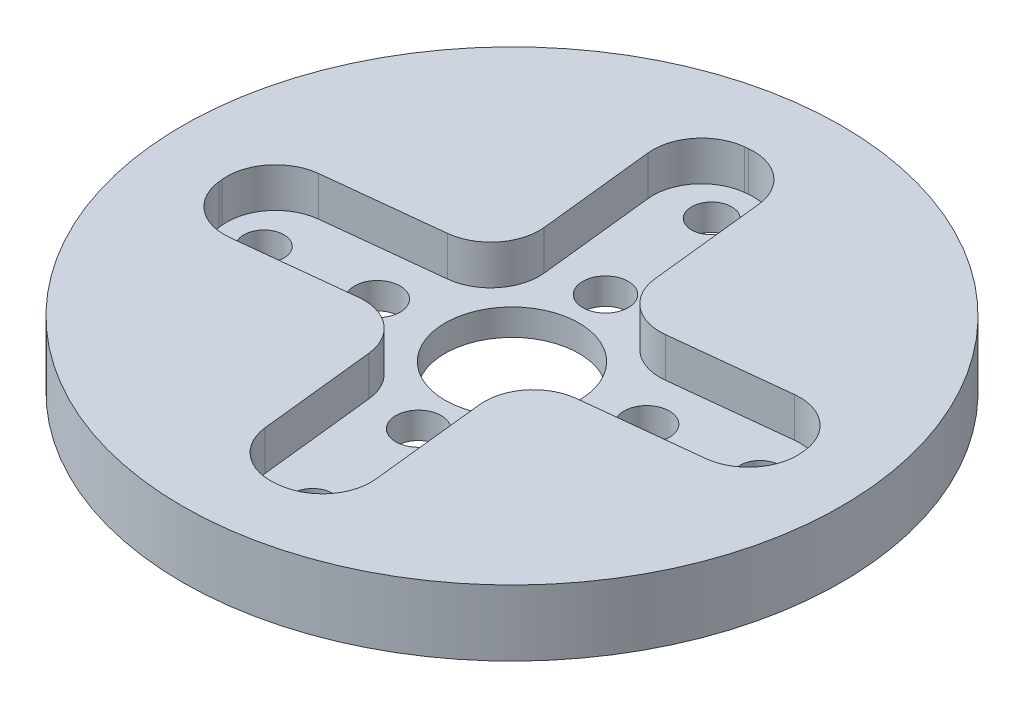
SolidWorks part; units mm, degrees
ref_plane "前基準面" through (0, 0, 0) normal (0, 0, 1) x (1, 0, 0)
ref_plane "上基準面" through (0, 0, 0) normal (0, 1, 0) x (1, 0, 0)
ref_plane "右基準面" through (0, 0, 0) normal (1, 0, 0) x (0, 0, -1)
sketch "草圖1" plane through (0, 0, 0) normal (0, 1, 0) x (1, 0, 0)
  line L38 (-19.9629, -2.0351) -> (-19.9356, -2.2876)
  line L39 (-15.8773, -5.5525) -> (-7.039, -4.5949)
  line L40 (-2.9807, -7.8598) -> (-2.0232, -16.6981)
  line L41 (2.0351, -19.9629) -> (2.2876, -19.9356)
  line L42 (5.5525, -15.8773) -> (4.5949, -7.039)
  line L43 (7.8598, -2.9807) -> (16.6981, -2.0232)
  line L44 (19.9629, 2.0351) -> (19.9356, 2.2876)
  line L45 (15.8773, 5.5525) -> (7.039, 4.5949)
  line L46 (2.9807, 7.8598) -> (2.0232, 16.6981)
  line L47 (-2.0351, 19.9629) -> (-2.2876, 19.9356)
  line L48 (-5.5525, 15.8773) -> (-4.5949, 7.039)
  line L49 (-7.8598, 2.9807) -> (-16.6981, 2.0232)
  circle A0 centre (0, 0) radius 25
  arc A25 (-16.6981, 2.0232) -> (-19.9629, -2.0351) centre (-16.3014, -1.6384) ccw
  arc A26 (-19.9356, -2.2876) -> (-15.8773, -5.5525) centre (-16.274, -1.8909) ccw
  arc A27 (-2.9807, -7.8598) -> (-7.039, -4.5949) centre (-6.6423, -8.2565) ccw
  arc A28 (-2.0232, -16.6981) -> (2.0351, -19.9629) centre (1.6384, -16.3014) ccw
  arc A29 (2.2876, -19.9356) -> (5.5525, -15.8773) centre (1.8909, -16.274) ccw
  arc A30 (7.8598, -2.9807) -> (4.5949, -7.039) centre (8.2565, -6.6423) ccw
  arc A31 (16.6981, -2.0232) -> (19.9629, 2.0351) centre (16.3014, 1.6384) ccw
  arc A32 (19.9356, 2.2876) -> (15.8773, 5.5525) centre (16.274, 1.8909) ccw
  arc A33 (2.9807, 7.8598) -> (7.039, 4.5949) centre (6.6423, 8.2565) ccw
  arc A34 (2.0232, 16.6981) -> (-2.0351, 19.9629) centre (-1.6384, 16.3014) ccw
  arc A35 (-2.2876, 19.9356) -> (-5.5525, 15.8773) centre (-1.8909, 16.274) ccw
  arc A36 (-7.8598, 2.9807) -> (-4.5949, 7.039) centre (-8.2565, 6.6423) ccw
  point P3 (0, 0)
  dimension "D1" = 50
extrude "填料-伸長1" add sketch "草圖1" along normal blind 5
sketch "草圖3" plane through (0, 0, 0) normal (0, 1, 0) x (1, 0, 0)
  circle A0 centre (0, 0) radius 22.5
  circle A1 centre (16.9821, 1.8399) radius 1.524 construction
  circle A2 centre (9.2171, 0.9986) radius 1.7272 construction
  circle A3 centre (1.8399, -16.9821) radius 1.524 construction
  circle A4 centre (0.8618, -7.9545) radius 1.7272 construction
  circle A5 centre (0, 0) radius 5.08 construction
  circle A6 centre (-16.9821, -1.8399) radius 1.524 construction
  circle A7 centre (-9.2171, -0.9986) radius 1.7272 construction
  circle A8 centre (-1.8399, 16.9821) radius 1.524 construction
  circle A9 centre (-0.8618, 7.9545) radius 1.7272 construction
  circle A10 centre (16.9821, 1.8399) radius 1.524
  circle A11 centre (9.2171, 0.9986) radius 1.7272
  circle A12 centre (1.8399, -16.9821) radius 1.524
  circle A13 centre (0.8618, -7.9545) radius 1.7272
  circle A14 centre (0, 0) radius 5.08
  circle A15 centre (-16.9821, -1.8399) radius 1.524
  circle A16 centre (-9.2171, -0.9986) radius 1.7272
  circle A17 centre (-1.8399, 16.9821) radius 1.524
  circle A18 centre (-0.8618, 7.9545) radius 1.7272
  dimension "D1" = 45
extrude "填料-伸長2" add sketch "草圖3" along normal blind 2
